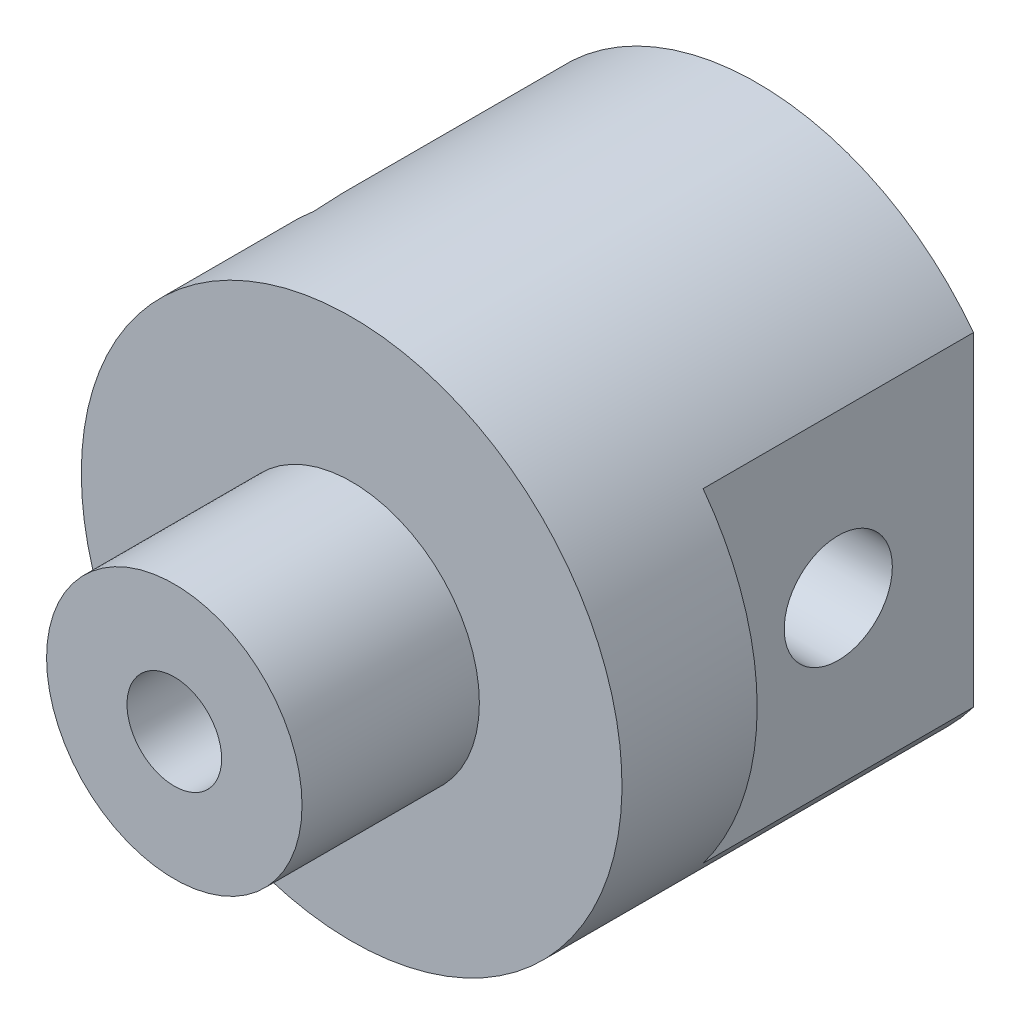
SolidWorks part; units mm, degrees
material "ABS"
ref_plane "Front Plane" through (0, 0, 0) normal (0, 0, 1) x (1, 0, 0)
ref_plane "Top Plane" through (0, 0, 0) normal (0, 1, 0) x (1, 0, 0)
ref_plane "Right Plane" through (0, 0, 0) normal (1, 0, 0) x (0, 0, -1)
sketch "Sketch1" plane through (0, 0, 0) normal (0, 0, 1) x (1, 0, 0)
  circle A0 centre (0, 0) radius 4.725
  dimension "D1" = 9.45
extrude "Boss-Extrude1" add sketch "Sketch1" against normal blind 6.56
sketch "Sketch5" plane through (0, 0, -6.56) normal (0, 0, -1) x (-1, 0, 0)
  circle A0 centre (0, 0) radius 10
  dimension "D1" = 20
extrude "Boss-Extrude3" add sketch "Sketch5" along normal blind 15
sketch "Sketch3" plane through (0, 0, 0) normal (1, 0, 0) x (0, 0, -1)
  line L0 (21.56, -5) -> (21.56, 5)
  line L2 (21.56, 0) -> (11.56, 0) construction
  line L3 (11.56, -7.6795) -> (11.56, 7.6795)
  line L4 (11.56, 7.6795) -> (21.56, 5)
  line L5 (11.56, -7.6795) -> (21.56, -5)
  line L9 (21.56, -10) -> (21.56, 10) construction
  point P11 (11.56, 0)
  dimension "D1" = 75
  dimension "D2" = 10
  dimension "D3" = 10
extrude "Cut-Extrude1" cut sketch "Sketch3" against normal blind 15 and the other way blind 5
sketch "Sketch4" plane through (0, 0, -21.56) normal (0, 0, -1) x (-1, 0, 0)
  line L0 (-10, 0) -> (0, 0) construction
  line L1 (-10, 6) -> (-8, 6)
  line L2 (-10, 6) -> (-10, -6)
  line L3 (-10, -6) -> (-8, -6)
  line L4 (-8, 6) -> (-8, -6)
  arc A1 (8.6603, 5) -> (8.6603, -5) centre (0, 0) ccw construction
  point P13 (-8, 0)
  dimension "D1" = 2
extrude "Cut-Extrude2" cut sketch "Sketch4" against normal up to surface (10 mm away) up to face at (-1.6013, 0, -11.56)
sketch "Sketch6" plane through (8, 0, 0) normal (1, 0, 0) x (0, 0, -1)
  line L0 (11.56, 6) -> (21.56, -6) construction
  circle A0 centre (16.56, 0) radius 2
  dimension "D1" = 4
extrude "Cut-Extrude3" cut sketch "Sketch6" against normal up to next
sketch "Sketch7" plane through (0, 0, 0) normal (0, 0, 1) x (1, 0, 0)
  circle A0 centre (0, 0) radius 1.75
  dimension "D1" = 3.5
extrude "Cut-Extrude4" cut sketch "Sketch7" against normal through all
